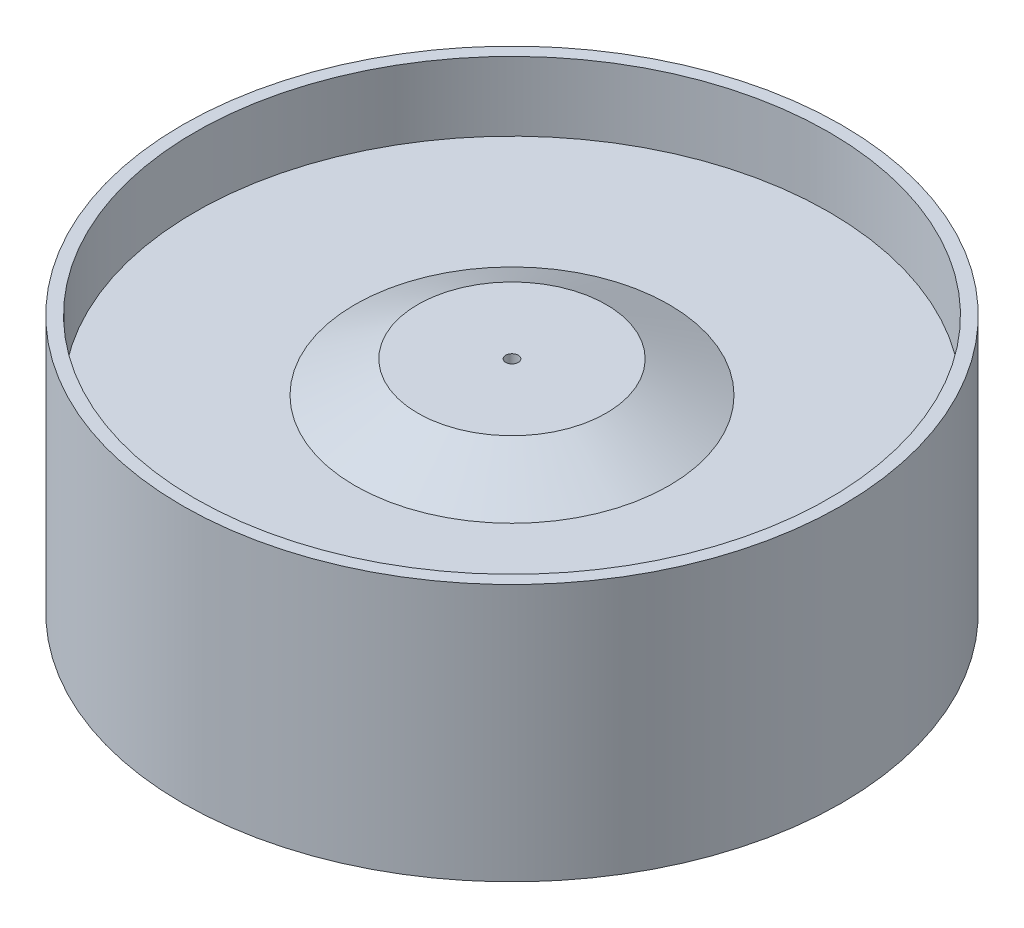
SolidWorks part; units mm, degrees
ref_plane "Front Plane" through (0, 0, 0) normal (0, 0, 1) x (1, 0, 0)
ref_plane "Top Plane" through (0, 0, 0) normal (0, 1, 0) x (1, 0, 0)
ref_plane "Right Plane" through (0, 0, 0) normal (1, 0, 0) x (0, 0, -1)
sketch "Sketch1" plane through (0, 0, 0) normal (0, 1, 0) x (1, 0, 0)
  circle A0 centre (0, 0) radius 52.5
  circle A1 centre (0, 0) radius 50.5
  dimension "D1" = 105
  dimension "D2" = 101
extrude "Main Blade Case Extrude" add sketch "Sketch1" along normal blind 41
ref_plane "First Plane" through (0, 21, 0) normal (0, -1, 0) x (-1, 0, 0)
sketch "Sketch2" plane through (0, 21, 0) normal (0, -1, 0) x (-1, 0, 0)
  circle A0 centre (0, 0) radius 50.5
extrude "Extrude for Goblet to Sit On" add sketch "Sketch2" against normal blind 9
sketch "Sketch4" plane through (0, 30, 0) normal (0, 1, 0) x (1, 0, 0)
  circle A0 centre (0, 0) radius 25
  dimension "D1" = 50
ref_plane "Second Plane" through (0, 35, 0) normal (0, 1, 0) x (1, 0, 0)
sketch "Sketch5" plane through (0, 35, 0) normal (0, 1, 0) x (1, 0, 0)
  circle A0 centre (0, 0) radius 15
  dimension "D1" = 30
loft "Rounded Middle Section" add profiles "Sketch5", "Sketch4"
sketch "Sketch8" plane through (0, 21, 0) normal (0, -1, 0) x (1, 0, 0)
  circle A0 centre (0, 0) radius 33
  circle A1 centre (0, 0) radius 32
  dimension "D1" = 66
  dimension "D2" = 64
extrude "Main Lower Extrude" add sketch "Sketch8" along normal blind 10
sketch "Sketch9" plane through (0, 21, 0) normal (0, -1, 0) x (1, 0, 0)
  circle A0 centre (0, 0) radius 32
  circle A1 centre (0, 0) radius 25
  dimension "D1" = 64
  dimension "D2" = 50
extrude "Second Lower Extrude" add sketch "Sketch9" along normal blind 6
sketch "Sketch12" plane through (0, 21, 0) normal (0, -1, 0) x (-1, 0, 0)
  circle A0 centre (0, 0) radius 25
extrude "Third Lower Extrude" add sketch "Sketch12" along normal blind 5
sketch "Sketch13" plane through (0, 16, 0) normal (0, -1, 0) x (1, 0, 0)
  circle A0 centre (0, 0) radius 1
  dimension "D1" = 2
extrude "Hole for Screw (Blade Casing)" cut sketch "Sketch13" against normal blind 89
